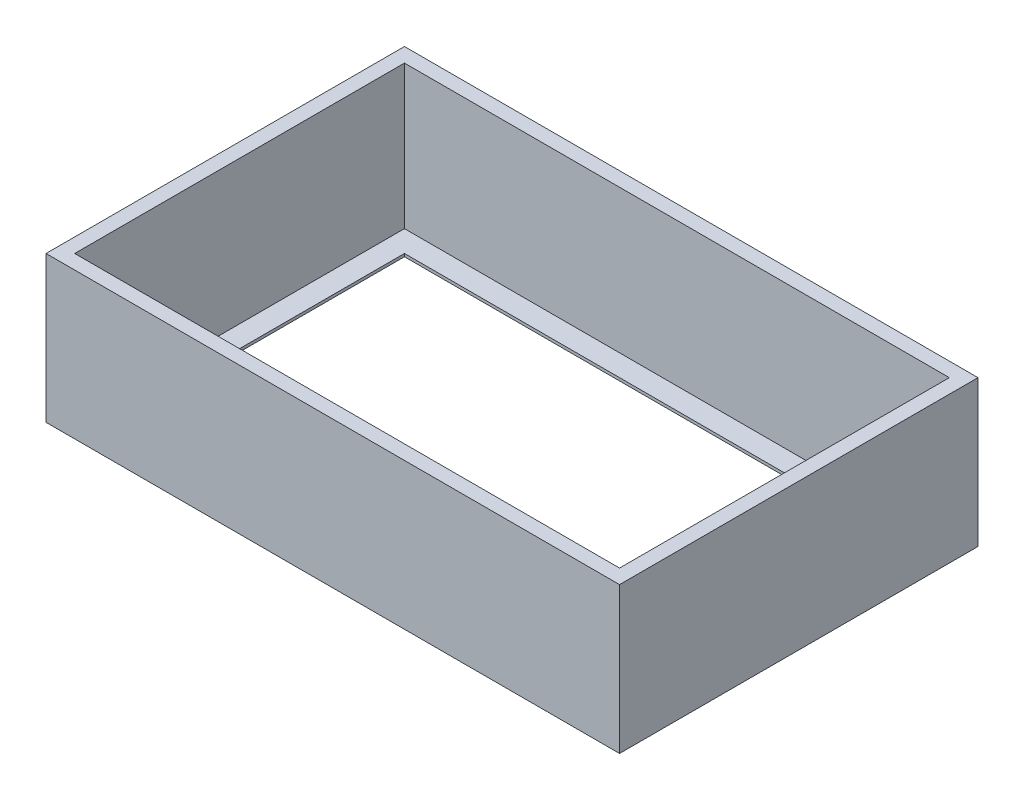
SolidWorks part; units mm, degrees
ref_plane "Front Plane" through (0, 0, 0) normal (0, 0, 1) x (1, 0, 0)
ref_plane "Top Plane" through (0, 0, 0) normal (0, 1, 0) x (1, 0, 0)
ref_plane "Right Plane" through (0, 0, 0) normal (1, 0, 0) x (0, 0, -1)
sketch "Sketch1" plane through (0, 0, 0) normal (0, 1, 0) x (1, 0, 0)
  line L1 (0.9738, -0.7755) -> (80.9738, -0.7755)
  line L2 (0.9738, -0.7755) -> (0.9738, -50.7755)
  line L3 (0.9738, -50.7755) -> (80.9738, -50.7755)
  line L4 (80.9738, -0.7755) -> (80.9738, -50.7755)
  dimension "D1" = 50
  dimension "D2" = 80
extrude "Boss-Extrude1" add sketch "Sketch1" along normal blind 0.4
sketch "Sketch2" plane through (0, 0.4, 0) normal (0, 1, 0) x (1, 0, 0)
  line L0 (2.9738, -2.7755) -> (2.9738, -48.7755)
  line L1 (0.9738, -0.7755) -> (80.9738, -0.7755)
  line L2 (0.9738, -0.7755) -> (0.9738, -50.7755)
  line L3 (0.9738, -50.7755) -> (80.9738, -50.7755)
  line L4 (80.9738, -0.7755) -> (80.9738, -50.7755)
  line L5 (2.9738, -48.7755) -> (78.9738, -48.7755)
  line L6 (78.9738, -2.7755) -> (78.9738, -48.7755)
  line L7 (2.9738, -2.7755) -> (78.9738, -2.7755)
  dimension "D1" = 2
extrude "Boss-Extrude2" add sketch "Sketch2" along normal blind 20
sketch "Sketch3" plane through (0, 0, 0) normal (0, -1, 0) x (-1, 0, 0)
  line L0 (-5.9738, -5.7755) -> (-5.9738, -45.7755)
  line L1 (-80.9738, -0.7755) -> (-0.9738, -0.7755) construction
  line L2 (-0.9738, -0.7755) -> (-0.9738, -50.7755) construction
  line L3 (-0.9738, -50.7755) -> (-80.9738, -50.7755) construction
  line L4 (-80.9738, -50.7755) -> (-80.9738, -0.7755) construction
  line L5 (-5.9738, -45.7755) -> (-75.9738, -45.7755)
  line L6 (-75.9738, -5.7755) -> (-75.9738, -45.7755)
  line L7 (-5.9738, -5.7755) -> (-75.9738, -5.7755)
  dimension "D1" = 5
  dimension "D2" = 5
  dimension "D3" = 5
  dimension "D4" = 5
extrude "Cut-Extrude1" cut sketch "Sketch3" against normal through all
